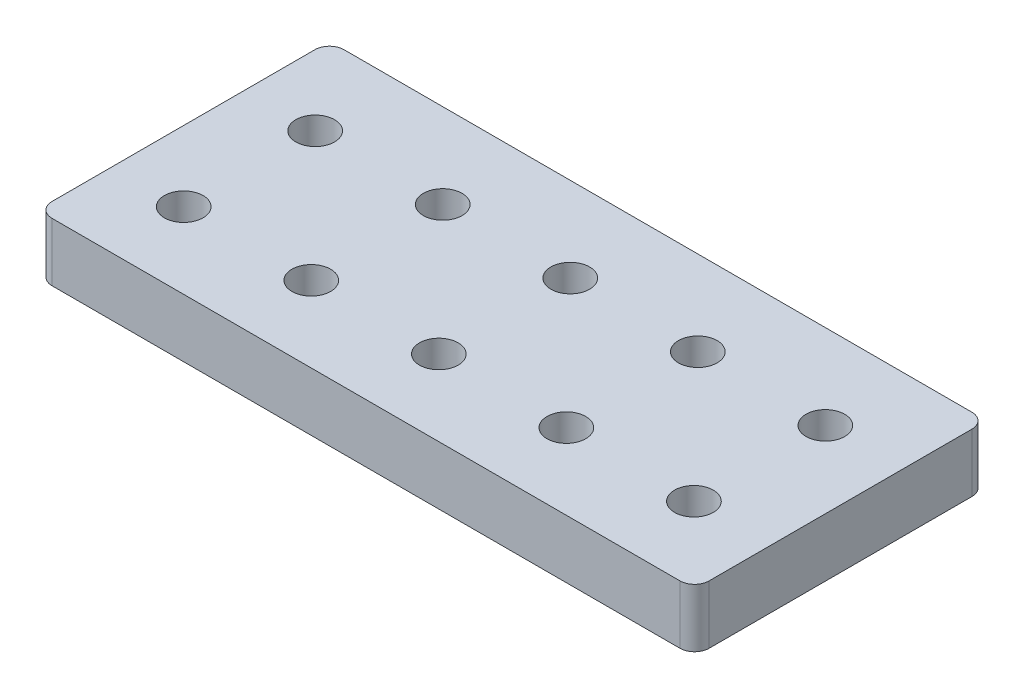
SolidWorks part; units mm, degrees
material "PVC Rigid"
ref_plane "Front Plane" through (0, 0, 0) normal (0, 0, 1) x (1, 0, 0)
ref_plane "Top Plane" through (0, 0, 0) normal (0, 1, 0) x (1, 0, 0)
ref_plane "Right Plane" through (0, 0, 0) normal (1, 0, 0) x (0, 0, -1)
sketch "Sketch1" plane through (0, 0, 0) normal (0, 1, 0) x (1, 0, 0)
  line L1 (-12.7, 0) -> (-558.8, 0)
  line L2 (0, 12.7) -> (0, 241.3)
  line L3 (-12.7, 254) -> (-558.8, 254)
  line L4 (-571.5, 12.7) -> (-571.5, 241.3)
  arc A0 (-12.7, 0) -> (0, 12.7) centre (-12.7, 12.7) ccw
  arc A1 (0, 241.3) -> (-12.7, 254) centre (-12.7, 241.3) ccw
  arc A2 (-558.8, 254) -> (-571.5, 241.3) centre (-558.8, 241.3) ccw
  arc A3 (-558.8, 0) -> (-571.5, 12.7) centre (-558.8, 12.7) cw
  point P7 (0, 0)
  dimension "D1" = 12.7
  dimension "D2" = 571.5
  dimension "D3" = 254
extrude "Boss-Extrude1" add sketch "Sketch1" along normal blind 50.8
sketch "Sketch2" plane through (0, 0, 0) normal (0, 1, 0) x (1, 0, 0)
  line L0 (0, 12.7) -> (-9.906, 12.7) construction
  line L1 (-571.5, 241.3) -> (-571.5, 12.7) construction
  line L2 (-510.286, 180.34) -> (-66.5708, 180.34) construction
  line L3 (0, 12.7) -> (0, 241.3) construction
  line L4 (-66.5708, 15.24) -> (-66.5708, 66.04) construction
  line L5 (-510.286, 66.04) -> (-66.5708, 66.04) construction
  line L6 (-510.286, 180.34) -> (-510.286, 66.04) construction
  line L7 (-66.5708, 66.04) -> (-66.5708, 180.34) construction
  circle A0 centre (-177.4996, 66.04) radius 50.8
  circle A1 centre (-66.5708, 66.04) radius 50.8
  circle A2 centre (-288.4284, 66.04) radius 50.8
  circle A3 centre (-399.3572, 66.04) radius 50.8
  circle A4 centre (-510.286, 66.04) radius 50.8
  circle A5 centre (-177.4996, 180.34) radius 50.8
  circle A6 centre (-288.4284, 180.34) radius 50.8
  circle A7 centre (-399.3572, 180.34) radius 50.8
  circle A8 centre (-510.286, 180.34) radius 50.8
  circle A9 centre (-66.5708, 180.34) radius 50.8
  dimension "D2" = 5
  dimension "D6" = 114.3
  dimension "D9" = 101.6
  dimension "D1" = 66.5708
  dimension "D5" = 9.906
  dimension "D3" = 2
  dimension "D7" = 61.214
  dimension "D8" = 443.7152
extrude "Cut-Extrude1" cut sketch "Sketch2" along normal blind 10.16
sketch "Sketch3" plane through (0, 10.16, 0) normal (0, -1, 0) x (1, 0, 0)
  line L0 (-66.5708, -129.54) -> (-66.5708, -116.84) construction
  line L1 (-66.5708, -123.19) -> (-571.5, -123.19) construction
  line L2 (-571.5, -241.3) -> (-571.5, -12.7) construction
  circle A0 centre (-66.5708, -180.34) radius 11.43
  circle A1 centre (-177.4996, -180.34) radius 11.43
  circle A2 centre (-288.4284, -180.34) radius 11.43
  circle A3 centre (-399.3572, -180.34) radius 11.43
  circle A4 centre (-510.286, -180.34) radius 11.43
  circle A5 centre (-66.5708, -180.34) radius 50.8 construction
  circle A6 centre (-66.5708, -180.34) radius 50.8 construction
  circle A7 centre (-66.5708, -66.04) radius 50.8 construction
  circle A8 centre (-510.286, -66.04) radius 11.43
  circle A9 centre (-399.3572, -66.04) radius 11.43
  circle A10 centre (-288.4284, -66.04) radius 11.43
  circle A11 centre (-177.4996, -66.04) radius 11.43
  circle A12 centre (-66.5708, -66.04) radius 11.43
  dimension "D1" = 22.86
extrude "Cut-Extrude2" cut sketch "Sketch3" against normal through all
sketch "Sketch6" plane through (0, 0, -254) normal (0, 0, -1) x (-1, 0, 0)
  line L0 (0, 0) -> (66.5708, 0) construction
  line L1 (12.7, 0) -> (558.8, 0) construction
  line L2 (66.5708, 0) -> (177.4996, 0) construction
  line L3 (177.4996, 0) -> (288.4284, 0) construction
  line L4 (288.4284, 0) -> (399.3572, 0) construction
  line L5 (399.3572, 0) -> (510.286, 0) construction
  dimension "D1" = 110.9288
  dimension "D2" = 66.5708
sketch "Sketch7" plane through (0, 50.8, 0) normal (0, 1, 0) x (1, 0, 0)
  circle A0 centre (-66.5708, 180.34) radius 16.8275
  circle A1 centre (-66.5708, 66.04) radius 16.8275
  circle A2 centre (-177.4996, 66.04) radius 16.8275
  circle A3 centre (-288.4284, 66.04) radius 16.8275
  circle A4 centre (-399.3572, 66.04) radius 16.8275
  circle A5 centre (-510.286, 66.04) radius 16.8275
  circle A6 centre (-177.4996, 180.34) radius 16.8275
  circle A7 centre (-288.4284, 180.34) radius 16.8275
  circle A8 centre (-399.3572, 180.34) radius 16.8275
  circle A9 centre (-510.286, 180.34) radius 16.8275
  dimension "D1" = 33.655
extrude "Cut-Extrude3" cut sketch "Sketch7" against normal blind 35.56
sketch "Sketch8" plane through (0, 0, -254) normal (0, 0, -1) x (-1, 0, 0)
  line L0 (66.5708, 0) -> (66.5708, 11.43) construction
  line L1 (12.7, 50.8) -> (558.8, 50.8) construction
  line L2 (174.3246, 14.605) -> (174.3246, 38.735)
  line L3 (69.7458, 14.605) -> (69.7458, 38.735)
  line L4 (180.6746, 14.605) -> (180.6746, 38.735)
  line L5 (63.3958, 14.605) -> (63.3958, 38.735)
  line L6 (285.2534, 14.605) -> (285.2534, 38.735)
  line L7 (291.6034, 14.605) -> (291.6034, 38.735)
  line L8 (396.1822, 14.605) -> (396.1822, 38.735)
  line L9 (402.5322, 14.605) -> (402.5322, 38.735)
  line L10 (507.111, 14.605) -> (507.111, 38.735)
  line L11 (513.461, 14.605) -> (513.461, 38.735)
  arc A0 (63.3958, 14.605) -> (69.7458, 14.605) centre (66.5708, 14.605) ccw
  arc A1 (63.3958, 38.735) -> (69.7458, 38.735) centre (66.5708, 38.735) cw
  arc A2 (174.3246, 38.735) -> (180.6746, 38.735) centre (177.4996, 38.735) cw
  arc A3 (174.3246, 14.605) -> (180.6746, 14.605) centre (177.4996, 14.605) ccw
  arc A4 (285.2534, 38.735) -> (291.6034, 38.735) centre (288.4284, 38.735) cw
  arc A5 (285.2534, 14.605) -> (291.6034, 14.605) centre (288.4284, 14.605) ccw
  arc A6 (396.1822, 38.735) -> (402.5322, 38.735) centre (399.3572, 38.735) cw
  arc A7 (396.1822, 14.605) -> (402.5322, 14.605) centre (399.3572, 14.605) ccw
  arc A8 (507.111, 38.735) -> (513.461, 38.735) centre (510.286, 38.735) cw
  arc A9 (507.111, 14.605) -> (513.461, 14.605) centre (510.286, 14.605) ccw
  point P3 (66.5708, 41.91)
  point P13 (66.5708, 11.43)
  dimension "D3" = 3.175
  dimension "D4" = 3.175
  dimension "D1" = 11.43
  dimension "D2" = 8.89
  dimension "D5" = 6.35
  dimension "D6" = 5
